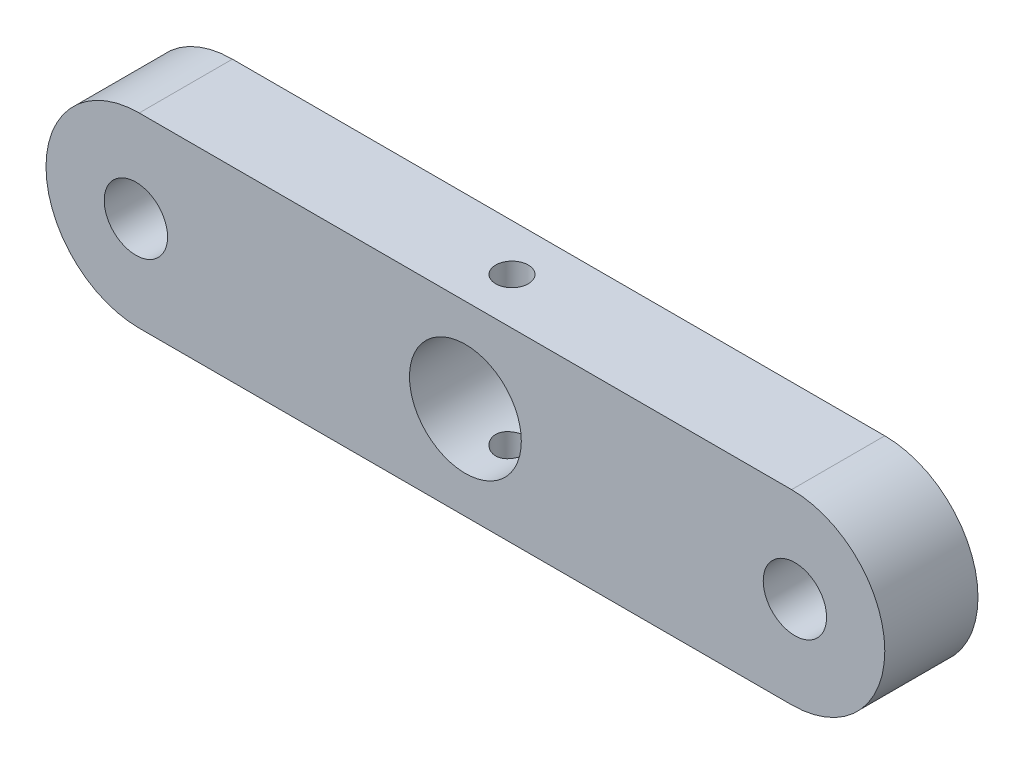
SolidWorks part; units mm, degrees
ref_plane "Front Plane" through (0, 0, 0) normal (0, 0, 1) x (1, 0, 0)
ref_plane "Top Plane" through (0, 0, 0) normal (0, 1, 0) x (1, 0, 0)
ref_plane "Right Plane" through (0, 0, 0) normal (1, 0, 0) x (0, 0, -1)
sketch "Sketch16" plane through (0, 0, 0) normal (0, 0, 1) x (1, 0, 0)
  line L0 (-35, 0) -> (35, 0) construction
  line L1 (-35, 10) -> (35, 10)
  line L2 (-35, -10) -> (35, -10)
  line L3 (0, -10) -> (0, 10) construction
  arc A0 (-35, 10) -> (-35, -10) centre (-35, 0) ccw
  arc A1 (35, -10) -> (35, 10) centre (35, 0) ccw
  circle A2 centre (-35.355, 0) radius 3.4
  circle A3 centre (0, 0) radius 6
  circle A4 centre (35.355, 0) radius 3.4
  point P2 (0, 0)
  point P13 (0, 0)
  point P17 (35.0695, -21.6824)
  dimension "D4" = 6.8
  dimension "D5" = 12
  dimension "D1" = 20
  dimension "D2" = 70
  dimension "D3" = 70.71
extrude "Boss-Extrude3" add sketch "Sketch16" along normal blind 10
hole_wizard "Ø3.5 (3.5) Diameter Hole1" positions "Sketch17" profile "Sketch18" hole size "Ø3.5" standard "ANSI Metric" end condition through all
sketch "Sketch17" plane through (0, 10, 0) normal (0, 1, 0) x (1, 0, 0)
  point P0 (0, -5)
  dimension "D1" = 5
sketch "Sketch18" plane through (0, 10, 5) normal (1, 0, 0) x (0, 0, 1)
  line L0 (0, 0) -> (0, 20)
  line L1 (0, 20) -> (1.75, 20)
  line L2 (1.75, 20) -> (1.75, 0)
  line L5 (1.75, 0) -> (0, 0)
  line L11 (0, -6.35) -> (0, 107.95) construction
  dimension "Thru Hole Dia." = 3.5
  dimension "Thru Hole Depth" = 20
